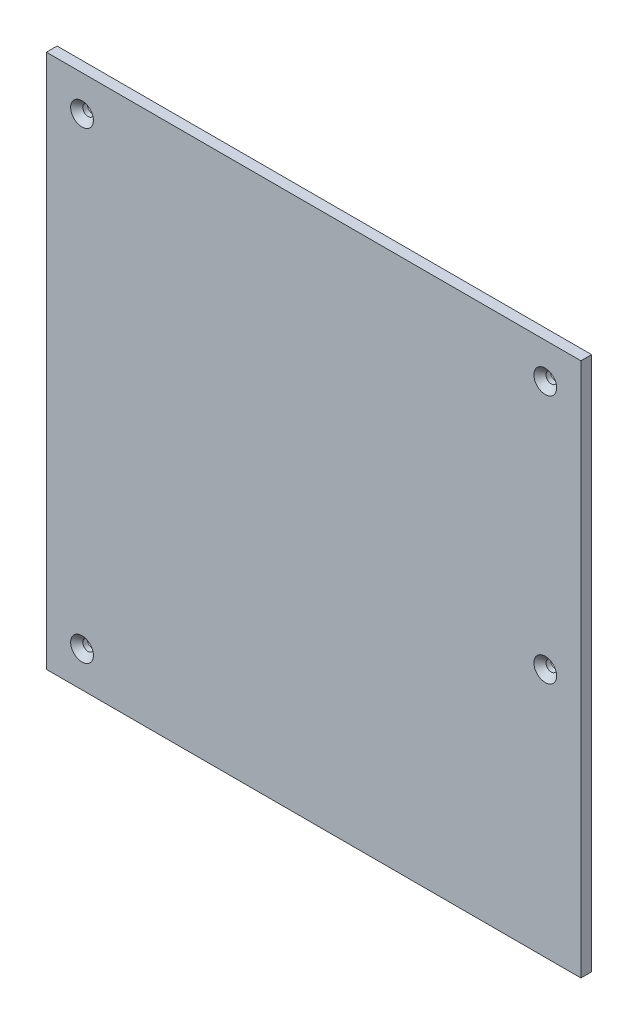
SolidWorks part; units mm, degrees
ref_plane "Plano frontal" through (0, 0, 0) normal (0, 0, 1) x (1, 0, 0)
ref_plane "Plano superior" through (0, 0, 0) normal (0, 1, 0) x (1, 0, 0)
ref_plane "Plano direito" through (0, 0, 0) normal (1, 0, 0) x (0, 0, -1)
sketch "Esboço1" plane through (0, 0, 0) normal (0, 0, 1) x (1, 0, 0)
  line L1 (-75, 75) -> (75, 75)
  line L2 (-75, 75) -> (-75, -75)
  line L3 (-75, -75) -> (75, -75)
  line L4 (75, 75) -> (75, -75)
  line L5 (-75, 75) -> (75, -75) construction
  line L6 (-75, -75) -> (75, 75) construction
  point P0 (0, 0)
  dimension "D1" = 150
extrude "Ressalto-extrusão1" add sketch "Esboço1" along normal blind 3
ref_plane "Plano1" through (0, 0, 0) normal (1, 0, 0) x (0, 0, -1)
ref_plane "Plano2" through (0, 0, 0) normal (0, 1, 0) x (1, 0, 0)
sketch "Esboço2" plane through (0, 0, 0) normal (0, 0, -1) x (-1, 0, 0)
  circle A0 centre (65, -65) radius 1.5 construction
  circle A1 centre (65, 65) radius 1.5 construction
  circle A2 centre (-65, 65) radius 1.5 construction
  circle A3 centre (-65, -5) radius 1.5 construction
  circle A4 centre (65, -65) radius 1.5
  circle A5 centre (65, 65) radius 1.5
  circle A6 centre (-65, 65) radius 1.5
  circle A7 centre (-65, -5) radius 1.5
extrude "Corte-extrusão1" cut sketch "Esboço2" against normal up to surface (3 mm away) up to face at (0, 0, 3)
chamfer "Chanfro1" distance 1.7 angle 45 4 edges at (-63.5, -65, 3) (66.5, -5, 3) (66.5, 65, 3) (-63.5, 65, 3)
